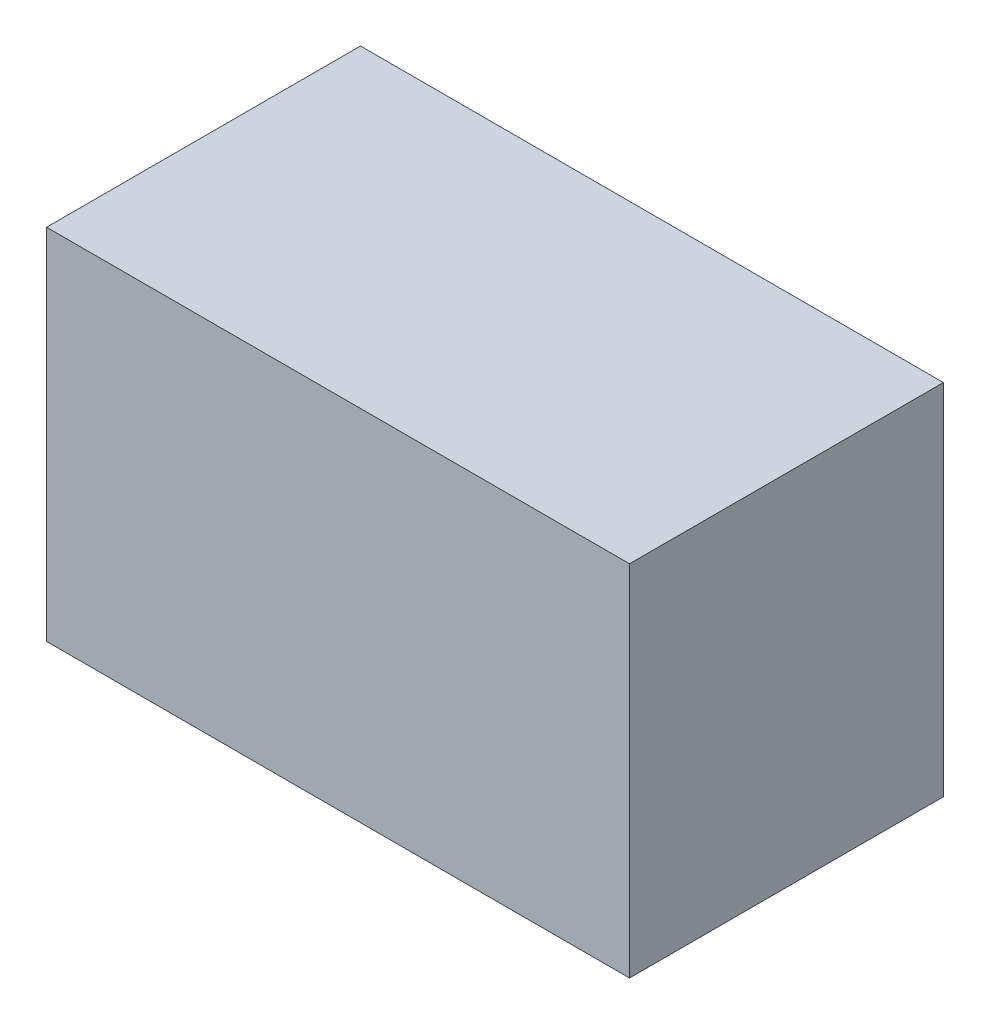
SolidWorks part; units mm, degrees
ref_plane "Front Plane" through (0, 0, 0) normal (0, 0, 1) x (1, 0, 0)
ref_plane "Top Plane" through (0, 0, 0) normal (0, 1, 0) x (1, 0, 0)
ref_plane "Right Plane" through (0, 0, 0) normal (1, 0, 0) x (0, 0, -1)
sketch "Sketch1" plane through (0, 0, 0) normal (0, 0, 1) x (1, 0, 0)
  line L0 (22.5, 4) -> (22.5, -4)
  line L1 (0, 0) -> (0, 11.3125) construction
  line L3 (-17.5, -17.5) -> (17.5, -17.5)
  line L4 (-17.5, -17.5) -> (-17.5, 17.5)
  line L5 (-17.5, 17.5) -> (17.5, 17.5)
  line L6 (17.5, -17.5) -> (17.5, 17.5)
  line L7 (-17.5, -17.5) -> (17.5, 17.5) construction
  line L8 (-17.5, 17.5) -> (17.5, -17.5) construction
  point P2 (22.5, 0)
  dimension "D1" = 8
  dimension "D2" = 45
  dimension "D3" = 35
sketch "Sketch2" plane through (0, 0, 0) normal (0, 0, 1) x (1, 0, 0)
  line L1 (-32.5, 37.1091) -> (32.5, 37.1091)
  line L2 (-32.5, 37.1091) -> (-32.5, 77.1091)
  line L3 (-32.5, 77.1091) -> (32.5, 77.1091)
  line L4 (32.5, 37.1091) -> (32.5, 77.1091)
  line L5 (-32.5, 37.1091) -> (32.5, 77.1091) construction
  line L6 (-32.5, 77.1091) -> (32.5, 37.1091) construction
  point P0 (0, 57.1091)
  dimension "D1" = 40
  dimension "D2" = 65
extrude "Boss-Extrude1" add sketch "Sketch2" along normal blind 35
